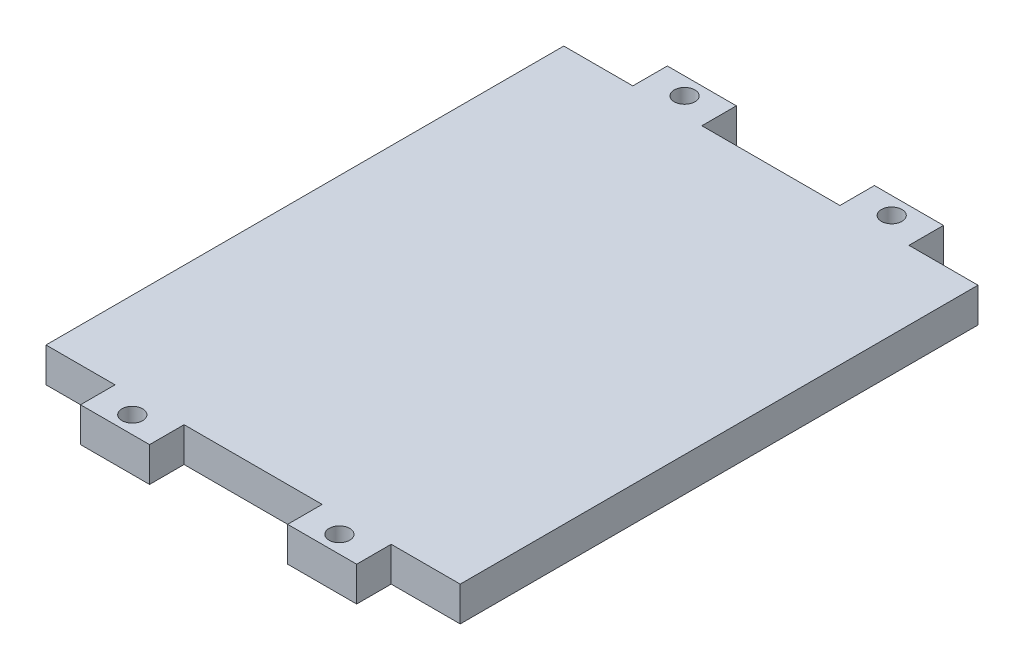
SolidWorks part; units mm, degrees
material "Beech"
ref_plane "Front Plane" through (0, 0, 0) normal (0, 0, 1) x (1, 0, 0)
ref_plane "Top Plane" through (0, 0, 0) normal (0, 1, 0) x (1, 0, 0)
ref_plane "Right Plane" through (0, 0, 0) normal (1, 0, 0) x (0, 0, -1)
sketch "Sketch1" plane through (0, 0, 0) normal (0, 1, 0) x (1, 0, 0)
  line L0 (-38.1, 53.975) -> (-38.1, -53.975)
  line L1 (-38.1, 53.975) -> (38.1, 53.975)
  line L2 (-38.1, -53.975) -> (38.1, -53.975)
  line L3 (38.1, 53.975) -> (38.1, -53.975)
  line L4 (-38.1, 53.975) -> (38.1, -53.975) construction
  line L5 (-38.1, -53.975) -> (38.1, 53.975) construction
  point P1 (0, 0)
  dimension "D1" = 107.95
  dimension "D2" = 76.2
extrude "Boss-Extrude1" add sketch "Sketch1" along normal blind 6.35
sketch "Sketch2" plane through (0, 6.35, 0) normal (0, 1, 0) x (1, 0, 0)
  line L0 (38.1, 53.975) -> (-38.1, 53.975) construction
  line L1 (-38.1, 53.975) -> (-25.4, 53.975)
  line L2 (-38.1, 53.975) -> (-38.1, 47.625)
  line L3 (-38.1, 47.625) -> (-25.4, 47.625)
  line L4 (-25.4, 53.975) -> (-25.4, 47.625)
  line L5 (-12.7, 53.975) -> (12.7, 53.975)
  line L6 (-12.7, 53.975) -> (-12.7, 47.625)
  line L7 (-12.7, 47.625) -> (12.7, 47.625)
  line L8 (12.7, 53.975) -> (12.7, 47.625)
  line L9 (0, 0) -> (28.6019, 0) construction
  line L10 (38.1, 53.975) -> (25.4, 53.975)
  line L11 (38.1, 53.975) -> (38.1, 47.625)
  line L12 (38.1, 47.625) -> (25.4, 47.625)
  line L13 (25.4, 53.975) -> (25.4, 47.625)
  line L14 (25.4, -53.975) -> (25.4, -47.625)
  line L15 (38.1, -47.625) -> (25.4, -47.625)
  line L16 (38.1, -53.975) -> (38.1, -47.625)
  line L17 (38.1, -53.975) -> (25.4, -53.975)
  line L18 (12.7, -53.975) -> (12.7, -47.625)
  line L19 (-12.7, -47.625) -> (12.7, -47.625)
  line L20 (-12.7, -53.975) -> (-12.7, -47.625)
  line L21 (-12.7, -53.975) -> (12.7, -53.975)
  line L22 (-25.4, -53.975) -> (-25.4, -47.625)
  line L23 (-38.1, -47.625) -> (-25.4, -47.625)
  line L24 (-38.1, -53.975) -> (-38.1, -47.625)
  line L25 (-38.1, -53.975) -> (-25.4, -53.975)
  line L26 (-38.1, 47.625) -> (38.1, 47.625) construction
  line L29 (19.05, 53.975) -> (25.4, 50.8) construction
  line L30 (25.4, 50.8) -> (12.7, 50.8) construction
  line L31 (-12.7, 50.8) -> (-25.4, 50.8) construction
  circle A0 centre (-19.05, 50.8) radius 1.7526
  circle A1 centre (19.05, 50.8) radius 1.7526
  circle A2 centre (19.05, -50.8) radius 1.7526
  circle A3 centre (-19.05, -50.8) radius 1.7526
  dimension "D8" = 3.5052
  dimension "D1" = 6.35
  dimension "D2" = 12.7
  dimension "D3" = 12.7
  dimension "D4" = 25.4
  dimension "D7" = 12.7
extrude "Cut-Extrude1" cut sketch "Sketch2" against normal blind 6.35
hole_wizard "#6 Clearance Hole1" positions "Sketch4" profile "Sketch3" hole size "#6" standard "ANSI Inch"
sketch "Sketch4" plane through (0, 6.35, 0) normal (0, 1, 0) x (1, 0, 0)
  point P0 (-19.05, 50.8)
  point P4 (19.05, 50.8)
  point P7 (-19.05, -50.8)
  point P10 (19.05, -50.8)
sketch "Sketch3" plane through (-19.05, 6.35, -50.8) normal (1, 0, 0) x (0, 0, 1)
  line L0 (0, 0) -> (0, 7.4908)
  line L1 (0, 7.4908) -> (1.8986, 6.35)
  line L2 (1.8986, 6.35) -> (1.8986, 0)
  line L5 (1.8986, 0) -> (0, 0)
  line L10 (0, 7.4908) -> (-1.8986, 6.35) construction
  line L11 (0, -6.35) -> (0, 107.95) construction
  dimension "Hole Dia." = 3.7973
  dimension "Hole Depth" = 6.35
  dimension "Drill Angle" = 118
